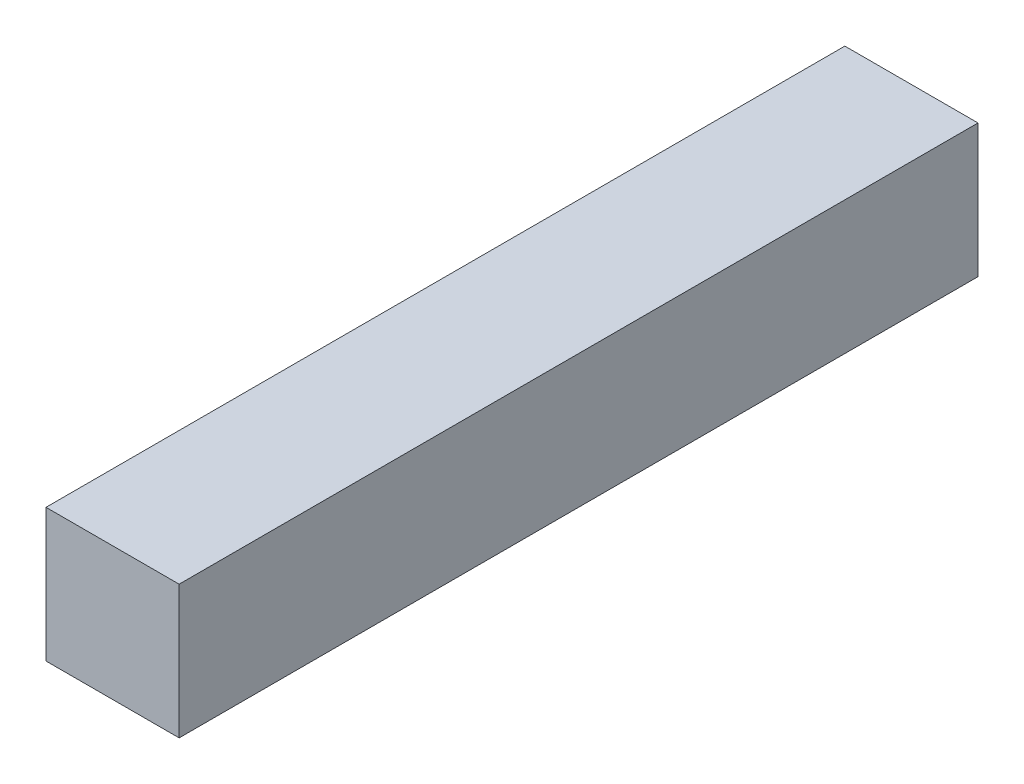
SolidWorks part; units mm, degrees
ref_plane "Front Plane" through (0, 0, 0) normal (0, 0, 1) x (1, 0, 0)
ref_plane "Top Plane" through (0, 0, 0) normal (0, 1, 0) x (1, 0, 0)
ref_plane "Right Plane" through (0, 0, 0) normal (1, 0, 0) x (0, 0, -1)
sketch "Sketch1" plane through (0, 0, 0) normal (0, 0, 1) x (1, 0, 0)
  line L0 (0, 33.7911) -> (0, -32.5815) construction
  line L1 (-54.1262, 0) -> (54.2774, 0) construction
  line L3 (-12.7, 12.7) -> (12.7, 12.7)
  line L4 (-12.7, 12.7) -> (-12.7, -12.7)
  line L5 (-12.7, -12.7) -> (12.7, -12.7)
  line L6 (12.7, 12.7) -> (12.7, -12.7)
  dimension "D1" = 25.4
  dimension "D2" = 25.4
  dimension "D3" = 12.7
  dimension "D4" = 12.7
extrude "Boss-Extrude1" add sketch "Sketch1" along normal blind 152.4
